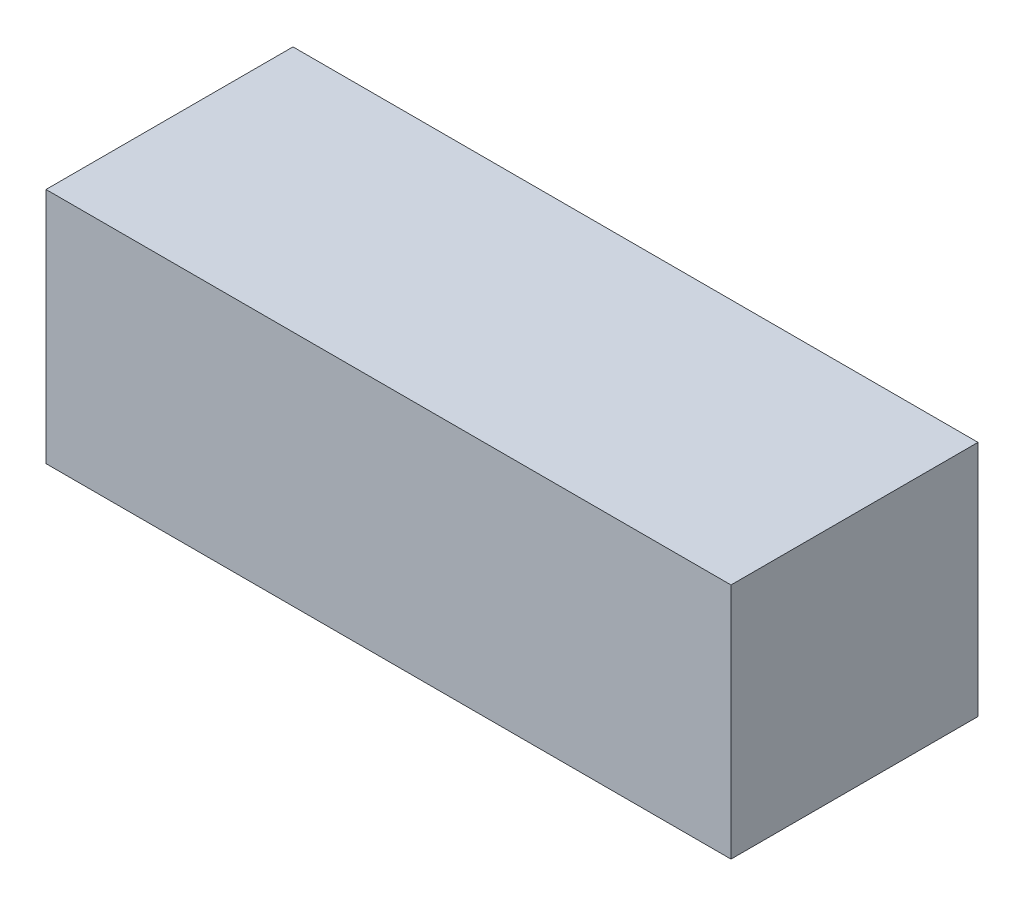
SolidWorks part; units mm, degrees
ref_plane "Front" through (0, 0, 0) normal (0, 0, 1) x (1, 0, 0)
ref_plane "Top" through (0, 0, 0) normal (0, 1, 0) x (1, 0, 0)
ref_plane "Right" through (0, 0, 0) normal (1, 0, 0) x (0, 0, -1)
sketch "Sketch1" plane through (0, 0, 0) normal (0, 1, 0) x (1, 0, 0)
  line L1 (-47.5975, -17.1626) -> (47.5975, -17.1626)
  line L2 (-47.5975, -17.1626) -> (-47.5975, 17.1626)
  line L3 (-47.5975, 17.1626) -> (47.5975, 17.1626)
  line L4 (47.5975, -17.1626) -> (47.5975, 17.1626)
  line L5 (-47.5975, -17.1626) -> (47.5975, 17.1626) construction
  line L6 (-47.5975, 17.1626) -> (47.5975, -17.1626) construction
  point P0 (0, 0)
extrude "Boss-Extrude1" add sketch "Sketch1" along normal blind 33
